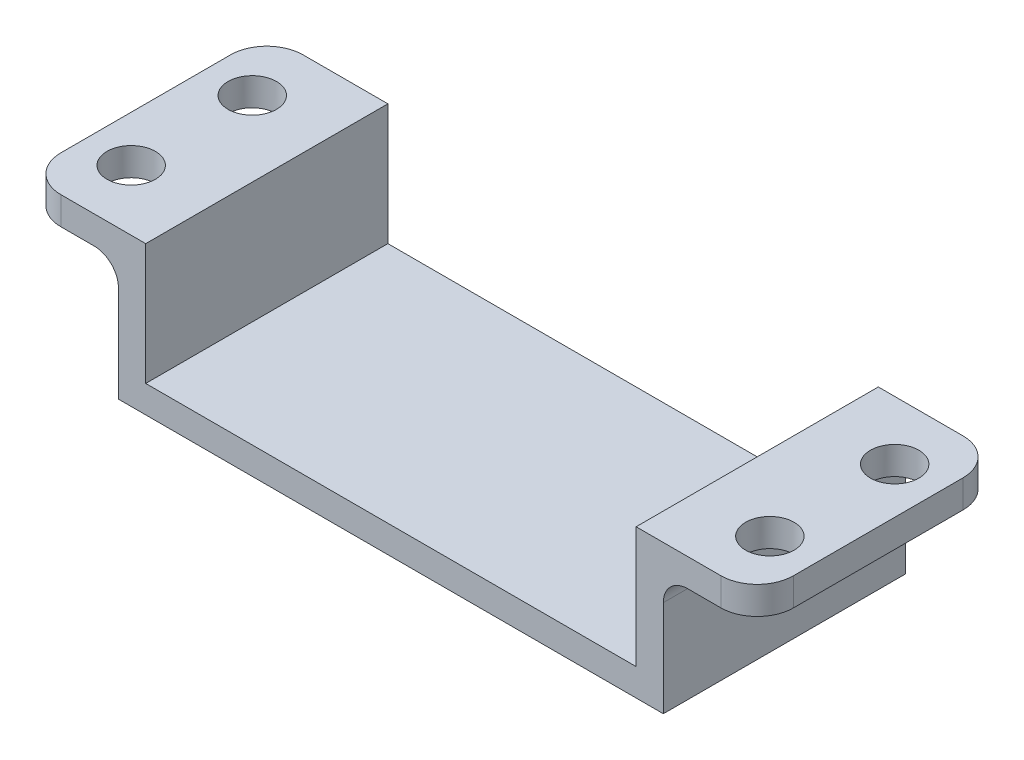
SolidWorks part; units mm, degrees
ref_plane "Front Plane" through (0, 0, 0) normal (0, 0, 1) x (1, 0, 0)
ref_plane "Top Plane" through (0, 0, 0) normal (0, 1, 0) x (1, 0, 0)
ref_plane "Right Plane" through (0, 0, 0) normal (1, 0, 0) x (0, 0, -1)
sketch "Sketch1" plane through (0, 0, 0) normal (0, 1, 0) x (1, 0, 0)
  line L1 (-22.5, -10) -> (22.5, -10)
  line L2 (-22.5, -10) -> (-22.5, 10)
  line L3 (-22.5, 10) -> (22.5, 10)
  line L4 (22.5, -10) -> (22.5, 10)
  line L5 (-22.5, -10) -> (22.5, 10) construction
  line L6 (-22.5, 10) -> (22.5, -10) construction
  point P0 (0, 0)
  dimension "D1" = 45
  dimension "D2" = 20
extrude "Boss-Extrude1" add sketch "Sketch1" along normal blind 2.25
sketch "Sketch2" plane through (0, 2.25, 0) normal (0, 1, 0) x (1, 0, 0)
  line L0 (-22.5, -10) -> (22.5, -10) construction
  line L1 (-22.5, 10) -> (-20.25, 10)
  line L2 (-22.5, 10) -> (-22.5, -10)
  line L3 (-22.5, -10) -> (-20.25, -10)
  line L4 (-20.25, 10) -> (-20.25, -10)
  line L6 (22.5, 10) -> (20.25, 10)
  line L7 (22.5, 10) -> (22.5, -10)
  line L8 (22.5, -10) -> (20.25, -10)
  line L9 (20.25, 10) -> (20.25, -10)
  dimension "D1" = 2.25
  dimension "D2" = 2.25
extrude "Boss-Extrude2" add sketch "Sketch2" along normal blind 10
sketch "Sketch3" plane through (0, 12.25, 0) normal (0, 1, 0) x (1, 0, 0)
  line L1 (-20.25, 10) -> (-30.25, 10)
  line L2 (-20.25, 10) -> (-20.25, -10)
  line L3 (-20.25, -10) -> (-30.25, -10)
  line L4 (-30.25, 10) -> (-30.25, -10)
  line L5 (20.25, 10) -> (30.25, 10)
  line L6 (20.25, 10) -> (20.25, -10)
  line L7 (20.25, -10) -> (30.25, -10)
  line L8 (30.25, 10) -> (30.25, -10)
  dimension "D1" = 10
  dimension "D2" = 10
extrude "Boss-Extrude3" add sketch "Sketch3" against normal blind 2.3
fillet "Fillet1" radius 2 2 edges at (22.5, 9.95, 0) (-22.5, 9.95, 0)
sketch "Sketch4" plane through (0, 12.25, 0) normal (0, 1, 0) x (1, 0, 0)
  line L0 (-69.1199, 0) -> (76.1978, 0) construction
  line L1 (-26.45, 17.4182) -> (-26.45, -16.8653) construction
  line L2 (26.45, 13.8793) -> (26.45, -18.7453) construction
  line L3 (-30.25, 10) -> (-30.25, -10) construction
  line L4 (30.25, -10) -> (30.25, 10) construction
  circle A0 centre (26.45, 5.1528) radius 2
  circle A1 centre (26.45, -5.1528) radius 2
  circle A2 centre (-26.45, 5) radius 2
  circle A3 centre (-26.45, -5) radius 2
  dimension "D3" = 4
  dimension "D1" = 3.8
  dimension "D2" = 3.8
  dimension "D4" = 5
extrude "Cut-Extrude1" cut sketch "Sketch4" against normal through all
sketch "Sketch5" plane through (0, 0, 0) normal (0, -1, 0) x (1, 0, 0)
  circle A0 centre (0, 0) radius 2.5
  dimension "D1" = 5
extrude "Boss-Extrude4" add sketch "Sketch5" along normal blind 7
fillet "Fillet2" radius 2 1 edges at (0, 0, -2.5)
fillet "Fillet3" radius 3 4 edges at (-30.25, 11.1, 10) (-30.25, 11.1, -10) (30.25, 11.1, -10) (30.25, 11.1, 10)
